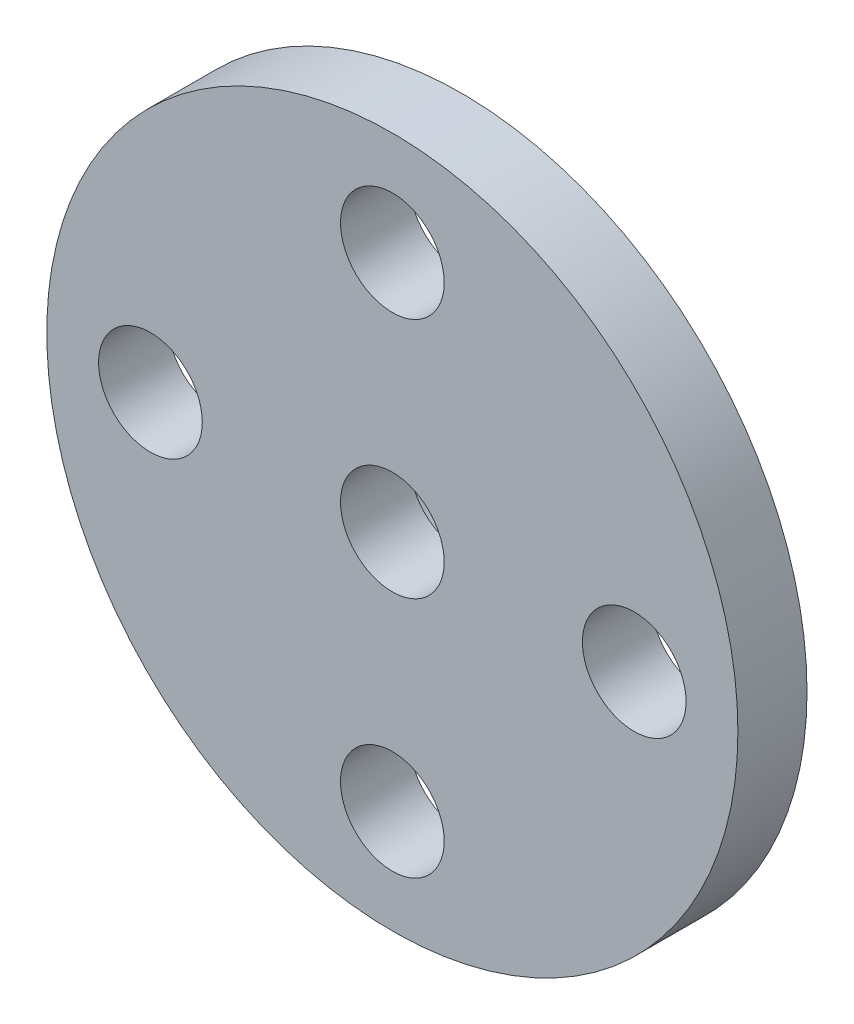
SolidWorks part; units mm, degrees
ref_plane "前视基准面" through (0, 0, 0) normal (0, 0, 1) x (1, 0, 0)
ref_plane "上视基准面" through (0, 0, 0) normal (0, 1, 0) x (1, 0, 0)
ref_plane "右视基准面" through (0, 0, 0) normal (1, 0, 0) x (0, 0, -1)
sketch "草图1" plane through (0, 0, 0) normal (0, 0, 1) x (1, 0, 0)
  circle A0 centre (0, 0) radius 10
  circle A1 centre (0, 0) radius 1.5
  circle A2 centre (0, 7) radius 1.5
  circle A3 centre (7, 0) radius 1.5
  circle A4 centre (0, -7) radius 1.5
  circle A5 centre (-7, 0) radius 1.5
  point P15 (0, 0)
  dimension "D1" = 4
extrude "凸台-拉伸1" add sketch "草图1" along normal blind 2
sketch "草图2" plane through (0, 0, 0) normal (0, 0, -1) x (-1, 0, 0)
  circle A0 centre (0, 0) radius 4.5
  circle A1 centre (0, 0) radius 3
extrude "凸台-拉伸2" add sketch "草图2" along normal blind 2
